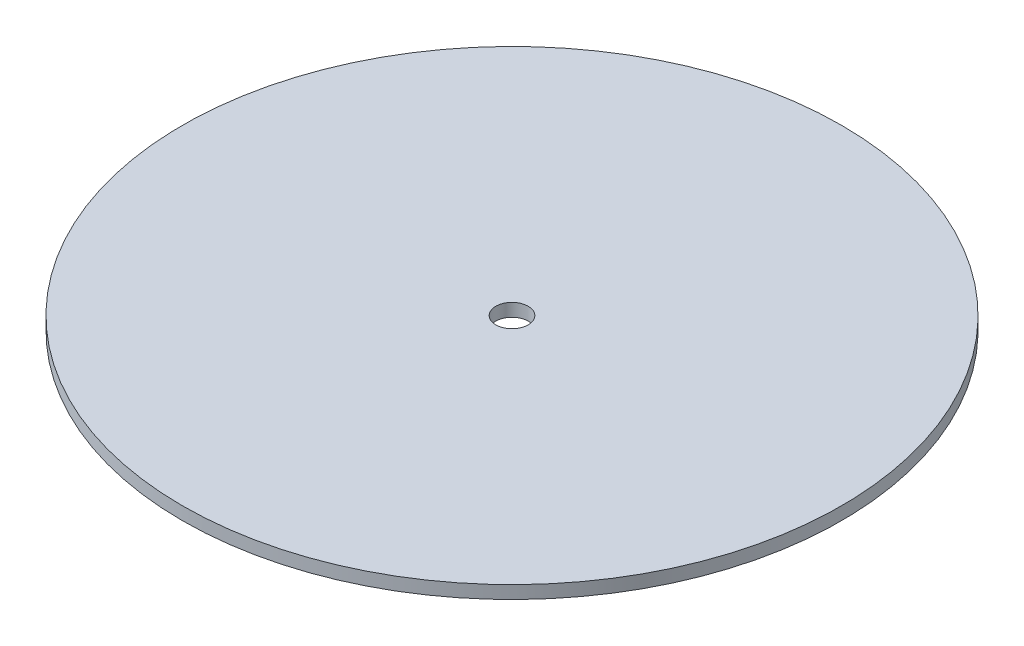
SolidWorks part; units mm, degrees
ref_plane "Спереди" through (0, 0, 0) normal (0, 0, 1) x (1, 0, 0)
ref_plane "Сверху" through (0, 0, 0) normal (0, 1, 0) x (1, 0, 0)
ref_plane "Справа" through (0, 0, 0) normal (1, 0, 0) x (0, 0, -1)
other "Configuration Table"
sketch "Эскиз4" plane through (0, 0, 0) normal (0, 1, 0) x (1, 0, 0)
  line L0 (0, 0) -> (-102, 0) construction
  line L1 (-102, 0) -> (102, 0) construction
  circle A0 centre (0, 0) radius 102
  circle A1 centre (0, 0) radius 5
  dimension "D1" = 204
  dimension "D2" = 10
extrude "Бобышка-Вытянуть1" add sketch "Эскиз4" along normal blind 4
